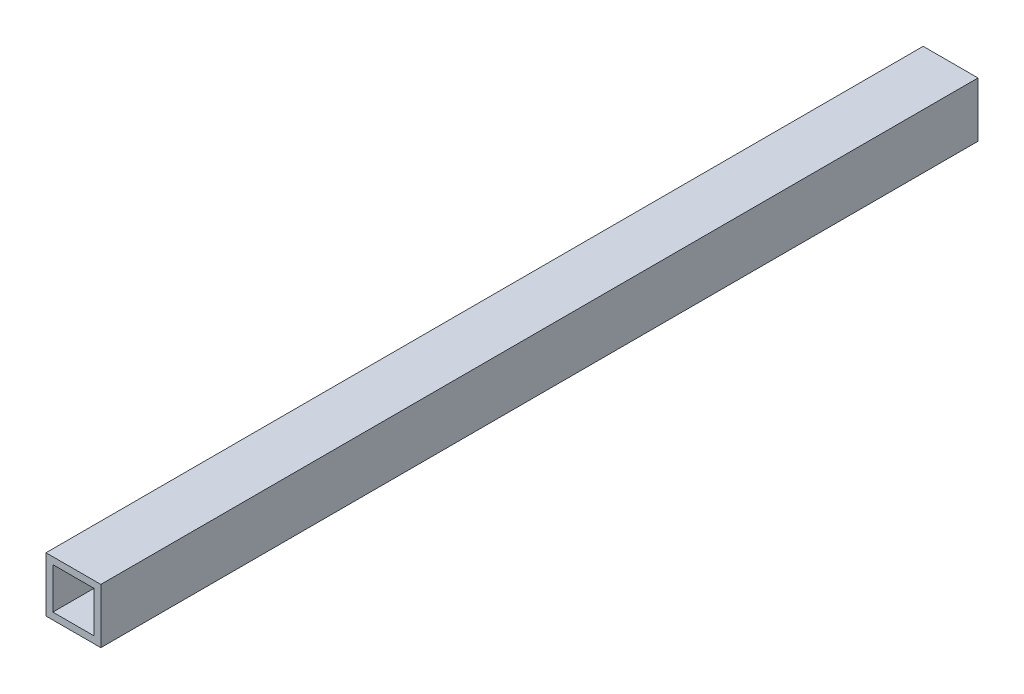
SolidWorks part; units mm, degrees
ref_plane "Front Plane" through (0, 0, 0) normal (0, 0, 1) x (1, 0, 0)
ref_plane "Top Plane" through (0, 0, 0) normal (0, 1, 0) x (1, 0, 0)
ref_plane "Right Plane" through (0, 0, 0) normal (1, 0, 0) x (0, 0, -1)
sketch "Sketch1" plane through (0, 0, 0) normal (0, 0, 1) x (1, 0, 0)
  line L0 (-9.525, 9.525) -> (9.525, 9.525)
  line L1 (-12.7, -12.7) -> (12.7, -12.7)
  line L2 (-12.7, -12.7) -> (-12.7, 12.7)
  line L3 (-12.7, 12.7) -> (12.7, 12.7)
  line L4 (12.7, -12.7) -> (12.7, 12.7)
  line L5 (-12.7, -12.7) -> (12.7, 12.7) construction
  line L6 (-12.7, 12.7) -> (12.7, -12.7) construction
  line L7 (9.525, -9.525) -> (9.525, 9.525)
  line L8 (-9.525, -9.525) -> (9.525, -9.525)
  line L9 (-9.525, -9.525) -> (-9.525, 9.525)
  point P0 (0, 0)
  dimension "D1" = 25.4
  dimension "D2" = 3.175
extrude "Boss-Extrude1" add sketch "Sketch1" along normal blind 406.4
